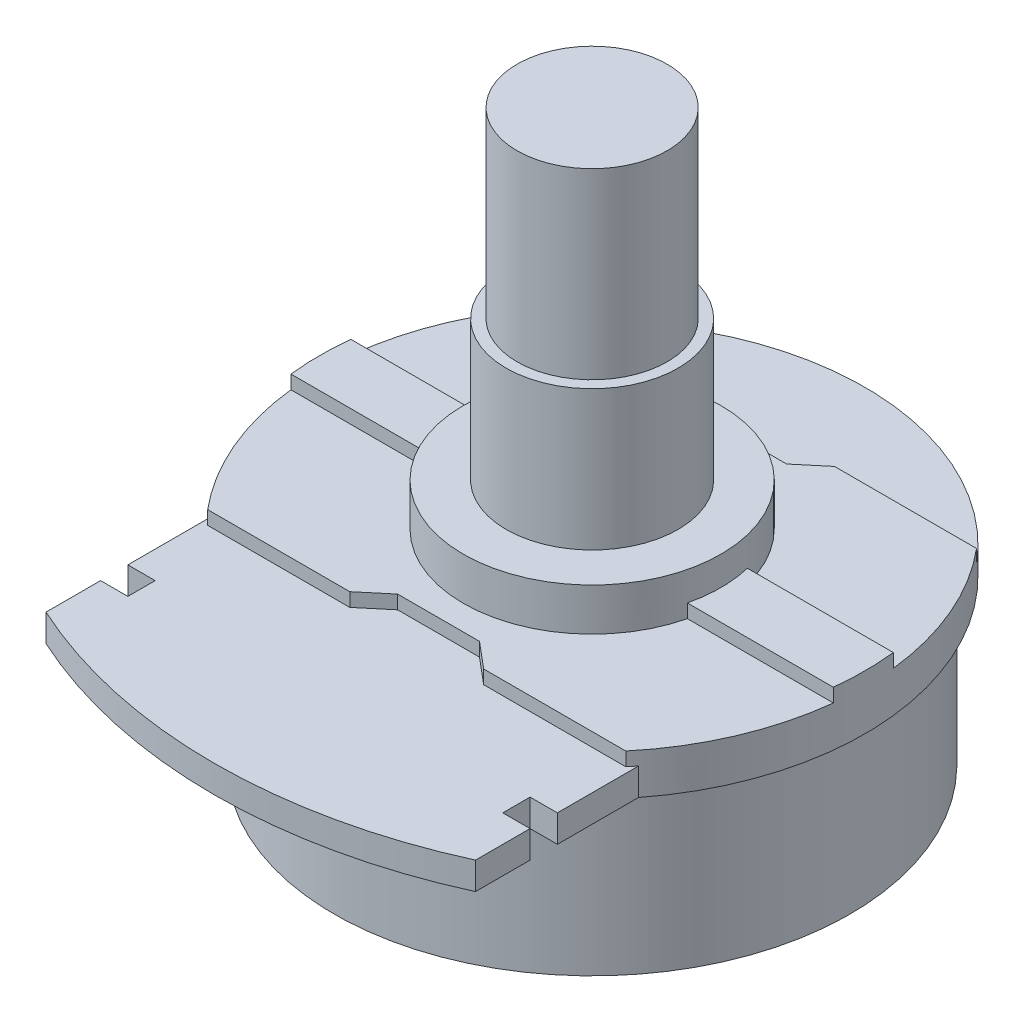
SolidWorks part; units mm, degrees
ref_plane "Front Plane" through (0, 0, 0) normal (0, 0, 1) x (1, 0, 0)
ref_plane "Top Plane" through (0, 0, 0) normal (0, 1, 0) x (1, 0, 0)
ref_plane "Right Plane" through (0, 0, 0) normal (1, 0, 0) x (0, 0, -1)
sketch "Sketch1" plane through (0, 0, 0) normal (0, 1, 0) x (1, 0, 0)
  circle A0 centre (0, 0) radius 12.0015
  dimension "D1" = 24.003
extrude "Boss-Extrude1" add sketch "Sketch1" along normal blind 7.62
sketch "Sketch2" plane through (0, 7.62, 0) normal (0, 1, 0) x (1, 0, 0)
  circle A0 centre (0, 0) radius 12.7
  dimension "D1" = 25.4
extrude "Boss-Extrude2" add sketch "Sketch2" along normal blind 1.27
sketch "Sketch3" plane through (0, 8.89, 0) normal (0, 1, 0) x (1, 0, 0)
  line L0 (0, 0) -> (0, 11.7211) construction
  line L1 (-9.9949, 0) -> (9.9949, 0)
  line L2 (-9.9949, 0) -> (-9.9949, -11.6123)
  line L3 (-9.9949, -18.796) -> (9.9949, -18.796)
  line L4 (9.9949, 0) -> (9.9949, -11.6123)
  line L5 (0, 0) -> (12.7, 0) construction
  line L6 (-9.9949, -12.8823) -> (-9.9949, -18.796)
  line L7 (-9.9949, -11.6123) -> (-8.7249, -11.6123)
  line L8 (9.9949, -12.8823) -> (9.9949, -18.796)
  line L9 (-9.9949, -12.8823) -> (-8.7249, -12.8823)
  line L10 (-8.7249, -11.6123) -> (-8.7249, -12.8823)
  line L11 (9.9949, -11.6123) -> (8.7249, -11.6123)
  line L13 (9.9949, -12.8823) -> (8.7249, -12.8823)
  line L14 (8.7249, -11.6123) -> (8.7249, -12.8823)
  circle A0 centre (0, 0) radius 12.7 construction
  arc A1 (-9.9949, -15.4223) -> (9.9949, -15.4223) centre (0, 6.4008) ccw
  point P7 (0, 0)
  point P15 (0, -17.6022)
  circle M1 centre (0, 0) radius 12.7
  dimension "D3" = 24.003
  dimension "D1" = 19.9898
  dimension "D2" = 18.796
  dimension "D4" = 1.1938
  dimension "D5" = 1.27
  dimension "D6" = 1.27
  dimension "D7" = 2.54
  dimension "D8" = 1.27
  dimension "D9" = 1.27
  dimension "D10" = 2.54
extrude "Boss-Extrude3" add sketch "Sketch3" against normal blind 1.27 contours L6 A1 L8 L13 L14 L11 L4 L2 L7 L10 L9 M1
sketch "Sketch4" plane through (0, 8.89, 0) normal (0, 1, 0) x (1, 0, 0)
  circle A0 centre (0, 0) radius 5.9944
  dimension "D1" = 11.9888
extrude "Boss-Extrude4" add sketch "Sketch4" along normal blind 2.6162
sketch "Sketch5" plane through (0, 11.5062, 0) normal (0, 1, 0) x (1, 0, 0)
  circle A0 centre (0, 0) radius 4.0005
  dimension "D1" = 8.001
extrude "Boss-Extrude5" add sketch "Sketch5" along normal blind 6.5024
sketch "Sketch6" plane through (0, 18.0086, 0) normal (0, 1, 0) x (1, 0, 0)
  circle A0 centre (0, 0) radius 3.4925
  dimension "D1" = 6.985
extrude "Boss-Extrude6" add sketch "Sketch6" along normal blind 8.509
sketch "Sketch7" plane through (0, 8.89, 0) normal (0, 1, 0) x (1, 0, 0)
  line L0 (-9.7288, 8.1634) -> (-3.1158, 8.1634)
  line L1 (-12.7, 0) -> (12.7, 0) construction
  line L2 (0, 12.7) -> (0, -17.6022) construction
  line L3 (-9.7288, 8.1634) -> (0, 0) construction
  line L4 (-9.7288, -8.1634) -> (-3.1158, -8.1634)
  line L5 (-9.7288, -8.1634) -> (0, 0) construction
  line L6 (-3.1158, 8.1634) -> (-1.905, 7.1474)
  line L7 (-1.905, 7.1474) -> (1.905, 7.1474)
  line L8 (1.905, 7.1474) -> (3.1158, 8.1634)
  line L9 (-3.1158, -8.1634) -> (-1.905, -7.1474)
  line L10 (-1.905, -7.1474) -> (1.905, -7.1474)
  line L11 (1.905, -7.1474) -> (3.1158, -8.1634)
  line L12 (3.1158, 8.1634) -> (9.7288, 8.1634)
  line L13 (3.1158, -8.1634) -> (9.7288, -8.1634)
  arc A0 (9.9949, -7.8353) -> (-9.9949, -7.8353) centre (0, 0) ccw construction
  arc A1 (-9.9949, -15.4223) -> (9.9949, -15.4223) centre (0, 6.4008) ccw construction
  circle A4 centre (0, 0) radius 5.9944 construction
  arc A5 (-9.7288, -8.1634) -> (-9.7288, 8.1634) centre (0, 0) cw
  arc A6 (9.7288, -8.1634) -> (9.7288, 8.1634) centre (0, 0) ccw
  point P23 (0, -7.1474)
  point P26 (0, 7.1474)
  point P31 (0, 5.9944)
  dimension "D1" = 40
  dimension "D7" = 12.7
  dimension "D12" = 12.7
  dimension "D2" = 40
  dimension "D3" = 40
  dimension "D4" = 40
  dimension "D5" = 40
  dimension "D6" = 40
  dimension "D8" = 1.016
  dimension "D9" = 3.81
  dimension "D10" = 3.81
  dimension "D11" = 1.016
extrude "Boss-Extrude7" add sketch "Sketch7" along normal blind 0.635
sketch "Sketch8" plane through (0, 9.525, 0) normal (0, 1, 0) x (1, 0, 0)
  line L0 (0, 0) -> (-12.7, 0) construction
  line L2 (-12.6229, 1.397) -> (12.6229, 1.397)
  line L4 (-12.6229, -1.397) -> (12.6229, -1.397)
  arc A0 (-9.7288, 8.1634) -> (-9.7288, -8.1634) centre (0, 0) ccw construction
  arc A1 (9.7288, -8.1634) -> (9.7288, 8.1634) centre (0, 0) ccw construction
  arc A2 (12.6229, 1.397) -> (12.6229, -1.397) centre (0, 0) cw
  arc A3 (-12.6229, 1.397) -> (-12.6229, -1.397) centre (0, 0) ccw
  dimension "D3" = 12.7
  dimension "D4" = 12.7
  dimension "D1" = 2.794
  dimension "D2" = 1.397
extrude "Boss-Extrude8" add sketch "Sketch8" along normal blind 0.635
